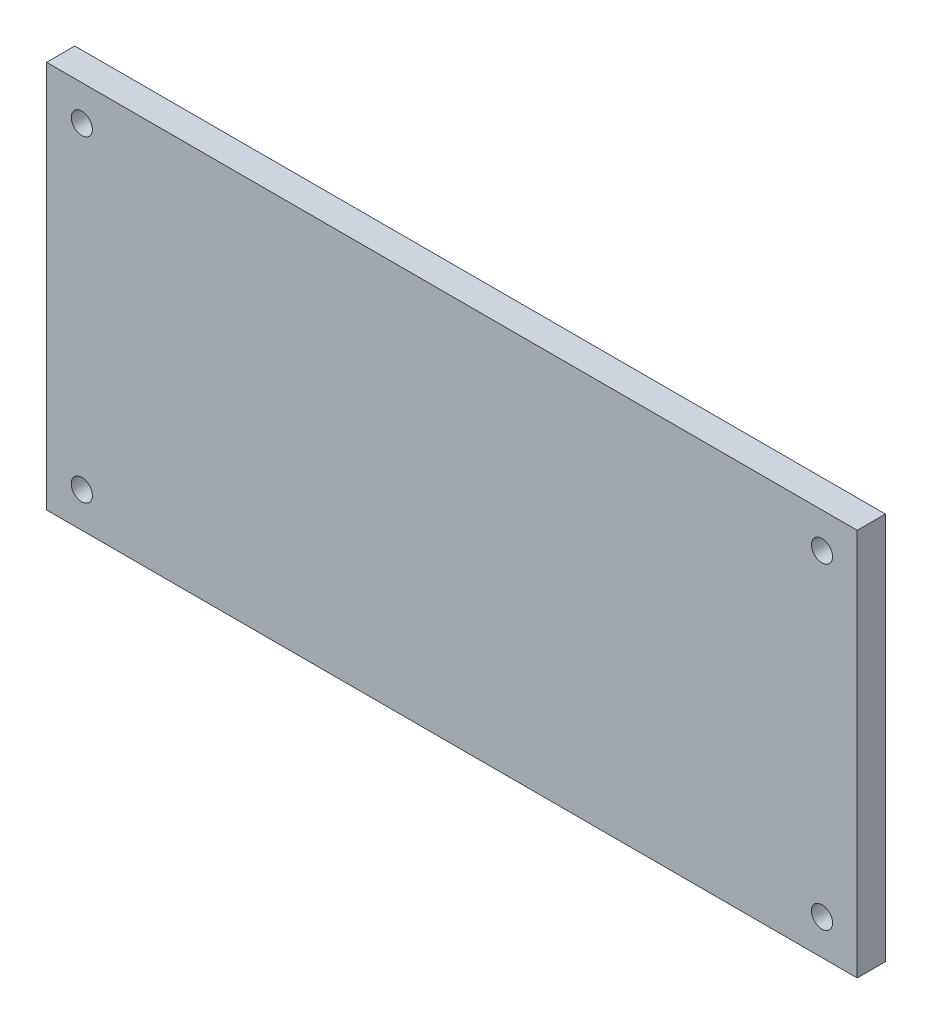
SolidWorks part; units mm, degrees
ref_plane "前视基准面" through (0, 0, 0) normal (0, 0, 1) x (1, 0, 0)
ref_plane "上视基准面" through (0, 0, 0) normal (0, 1, 0) x (1, 0, 0)
ref_plane "右视基准面" through (0, 0, 0) normal (1, 0, 0) x (0, 0, -1)
other "Configuration Table"
sketch "草图1" plane through (0, 0, 0) normal (0, 0, 1) x (1, 0, 0)
  line L1 (-115, 55) -> (115, 55)
  line L2 (-115, 55) -> (-115, -55)
  line L3 (-115, -55) -> (115, -55)
  line L4 (115, 55) -> (115, -55)
  line L5 (-115, 55) -> (115, -55) construction
  line L6 (-115, -55) -> (115, 55) construction
  point P0 (0, 0)
  dimension "D1" = 230
  dimension "D2" = 110
extrude "凸台-拉伸2" add sketch "草图1" along normal blind 8
sketch "草图2" plane through (0, 0, 8) normal (0, 0, 1) x (1, 0, 0)
  line L0 (115, 55) -> (-115, 55) construction
  line L1 (-115, 55) -> (-115, -55) construction
  line L2 (-115, -55) -> (115, -55) construction
  line L3 (115, -55) -> (115, 55) construction
  circle A0 centre (-105, 45) radius 3
  circle A1 centre (-105, -45) radius 3
  circle A2 centre (105, -45) radius 3
  circle A3 centre (105, 45) radius 3
  dimension "D1" = 6
  dimension "D4" = 6
  dimension "D7" = 6
  dimension "D10" = 6
  dimension "D2" = 10
  dimension "D3" = 10
  dimension "D5" = 10
  dimension "D6" = 10
  dimension "D8" = 10
  dimension "D9" = 10
  dimension "D11" = 10
  dimension "D12" = 10
extrude "切除-拉伸1" cut sketch "草图2" against normal up to surface (8 mm away) up to face at (0, 0, 0)
